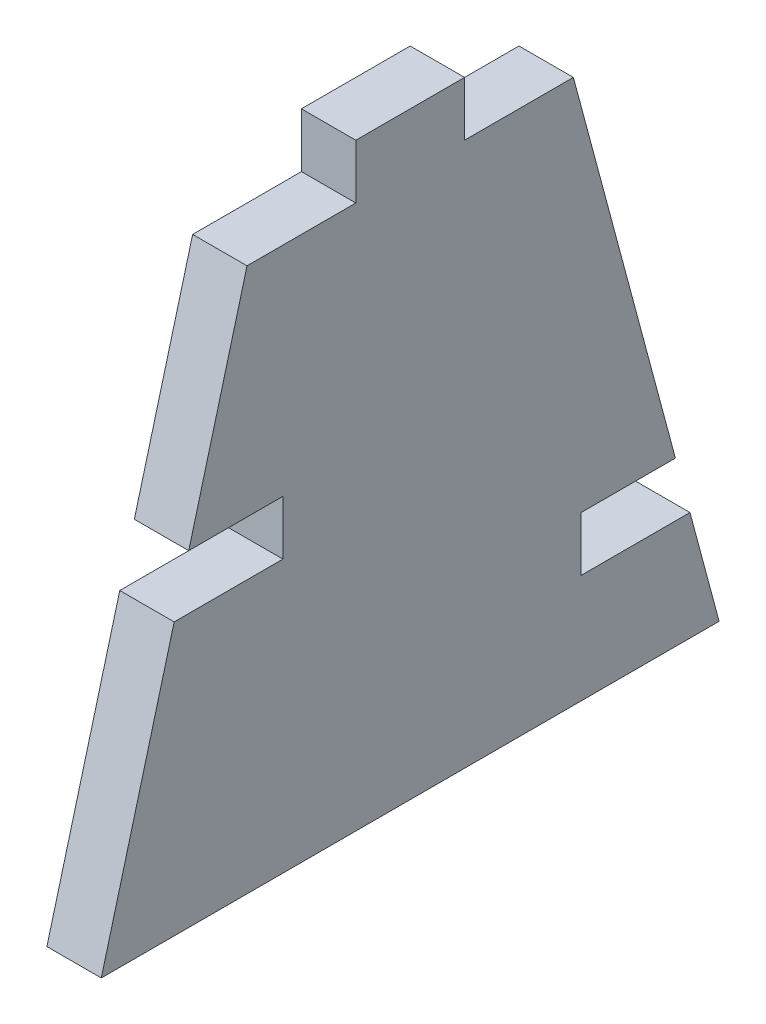
SolidWorks part; units mm, degrees
ref_plane "Front Plane" through (0, 0, 0) normal (0, 0, 1) x (1, 0, 0)
ref_plane "Top Plane" through (0, 0, 0) normal (0, 1, 0) x (1, 0, 0)
ref_plane "Right Plane" through (0, 0, 0) normal (1, 0, 0) x (0, 0, -1)
sketch "Sketch1" plane through (0, 0, 0) normal (1, 0, 0) x (0, 0, -1)
  line L0 (56.7949, 0) -> (-56.7949, 0)
  line L1 (-56.7949, 0) -> (-43.3975, 50)
  line L2 (-30, 100) -> (-10, 100)
  line L3 (-10, 100) -> (-10, 110)
  line L4 (-10, 110) -> (10, 110)
  line L5 (0, 0) -> (0, 49271.0681) construction
  line L6 (10, 100) -> (10, 110)
  line L7 (30, 100) -> (10, 100)
  line L8 (56.7949, 0) -> (51.4359, 20)
  line L9 (-40.718, 60) -> (-23.3975, 60)
  line L10 (-23.3975, 60) -> (-23.3975, 50)
  line L11 (-23.3975, 50) -> (-43.3975, 50)
  line L12 (48.7564, 30) -> (31.4359, 30)
  line L13 (31.4359, 30) -> (31.4359, 20)
  line L14 (31.4359, 20) -> (51.4359, 20)
  line L15 (-40.718, 60) -> (-30, 100)
  line L16 (48.7564, 30) -> (30, 100)
  point P10 (0, 110)
  point P13 (0, 0)
  dimension "D1" = 10
  dimension "D2" = 100
  dimension "D3" = 75
  dimension "D4" = 10
  dimension "D5" = 30
  dimension "D6" = 10
  dimension "D7" = 20
  dimension "D8" = 60
  dimension "D9" = 10
  dimension "D10" = 20
  dimension "D11" = 20
extrude "Boss-Extrude1" add sketch "Sketch1" along normal blind 10
